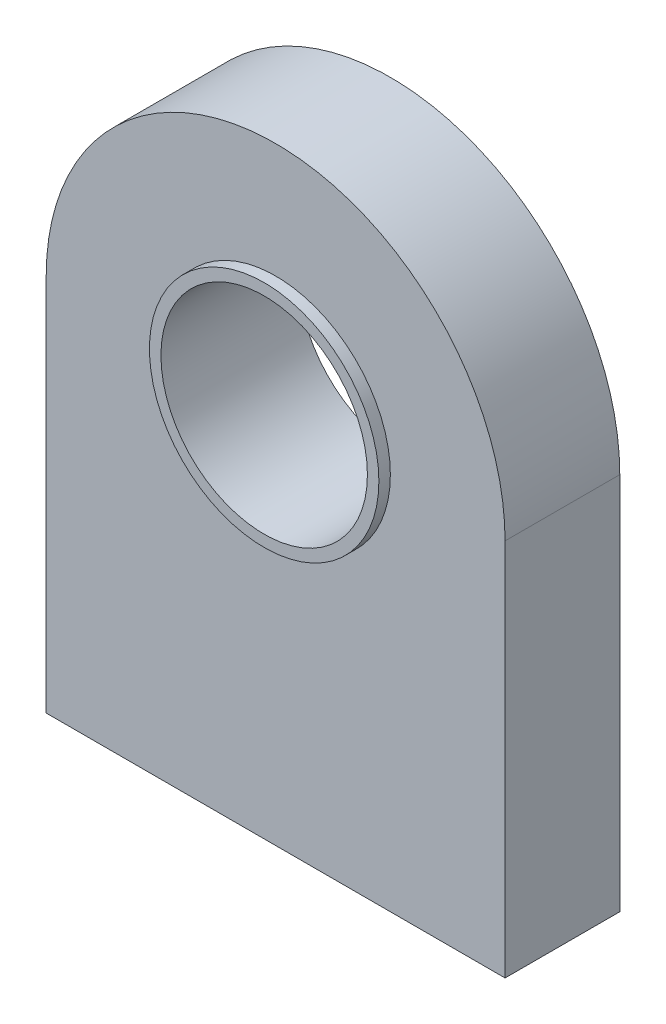
SolidWorks part; units mm, degrees
ref_plane "Alzado" through (0, 0, 0) normal (0, 0, 1) x (1, 0, 0)
ref_plane "Planta" through (0, 0, 0) normal (0, 1, 0) x (1, 0, 0)
ref_plane "Vista lateral" through (0, 0, 0) normal (1, 0, 0) x (0, 0, -1)
sketch "Croquis1" plane through (0, 0, 0) normal (0, 0, 1) x (1, 0, 0)
  line L0 (0, 0) -> (0, 16.5)
  line L1 (20, 16.5) -> (20, 0)
  line L2 (20, 0) -> (0, 0)
  line L3 (0, 6.5) -> (20, 6.5) construction
  arc A0 (0, 16.5) -> (20, 16.5) centre (10, 16.5) cw
  circle A1 centre (10, 16.5) radius 4.5
  dimension "D1" = 10
  dimension "D2" = 6.5
  dimension "D4" = 9
  dimension "D3" = 10
extrude "Saliente-Extruir1" add sketch "Croquis1" along normal blind 5
ref_plane "Plano1" through (0, 0, 2.5) normal (0, 0, 1) x (1, 0, 0)
sketch "Croquis2" plane through (0, 0, 2.5) normal (0, 0, 1) x (1, 0, 0)
  line L0 (10, 26.5) -> (10, 0) construction
  line L1 (0, 0) -> (20, 0) construction
  line L2 (0, 16.5) -> (20, 16.5) construction
  arc A0 (20, 16.5) -> (0, 16.5) centre (10, 16.5) ccw construction
  circle A1 centre (10, 16.5) radius 5
  circle A2 centre (10, 16.5) radius 4.5
  dimension "D1" = 9
  dimension "D2" = 10
extrude "Saliente-Extruir3" add sketch "Croquis2" along normal blind 3 and the other way blind 3
